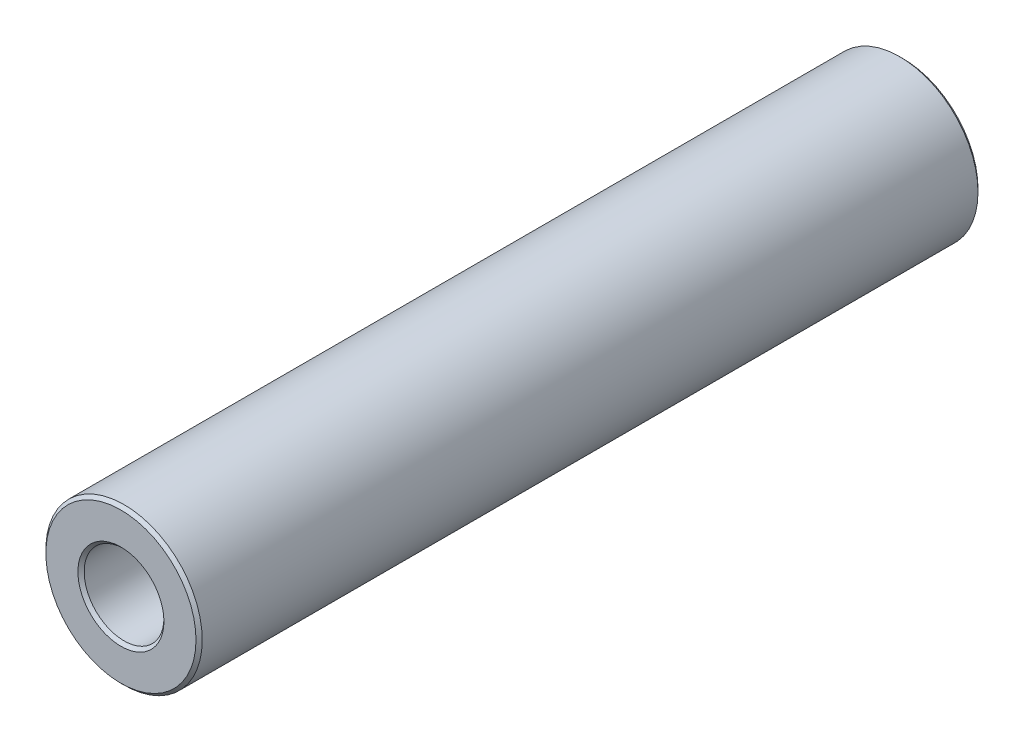
SolidWorks part; units mm, degrees
material "6061-T6 (SS)"
ref_plane "Front Plane" through (0, 0, 0) normal (0, 0, 1) x (1, 0, 0)
ref_plane "Top Plane" through (0, 0, 0) normal (0, 1, 0) x (1, 0, 0)
ref_plane "Right Plane" through (0, 0, 0) normal (1, 0, 0) x (0, 0, -1)
sketch "Sketch1" plane through (0, 0, 0) normal (0, 0, 1) x (1, 0, 0)
  circle A0 centre (0, 0) radius 2.55
  circle A1 centre (0, 0) radius 5
  dimension "D1" = 5.1
  dimension "D2" = 10
extrude "Boss-Extrude1" add sketch "Sketch1" along normal blind 50
chamfer "Chamfer1" distance 0.2 angle 45 4 edges at (5, 0, 0) (2.55, 0, 0) (2.55, 0, 50) (5, 0, 50)
